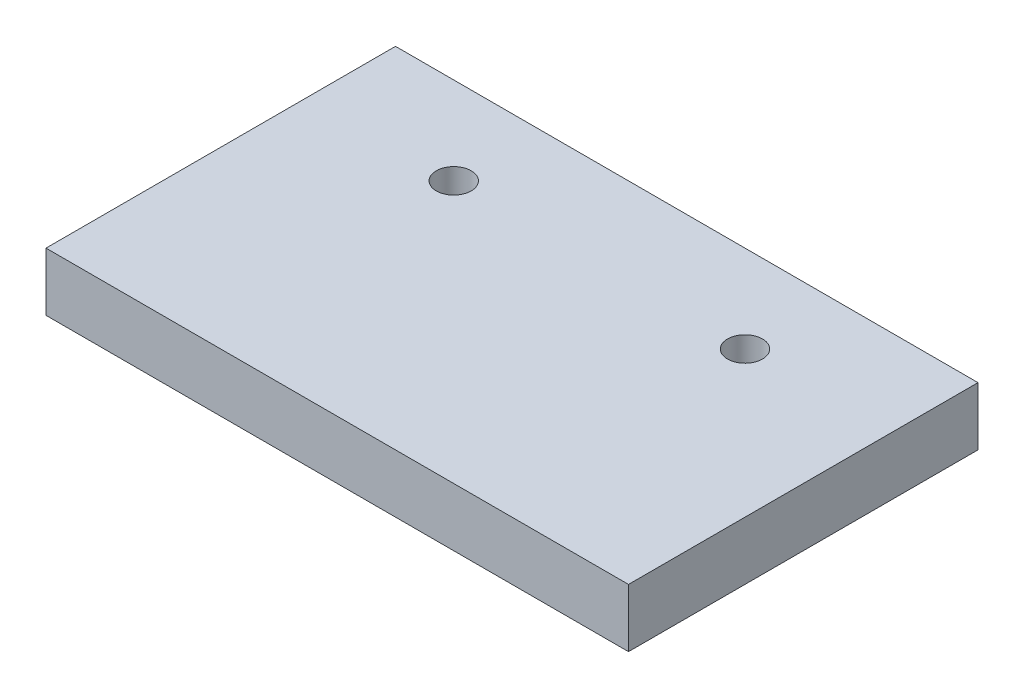
SolidWorks part; units mm, degrees
ref_plane "前视基准面" through (0, 0, 0) normal (0, 0, 1) x (1, 0, 0)
ref_plane "上视基准面" through (0, 0, 0) normal (0, 1, 0) x (1, 0, 0)
ref_plane "右视基准面" through (0, 0, 0) normal (1, 0, 0) x (0, 0, -1)
other "Configuration Table"
sketch "草图1" plane through (0, 0, 0) normal (0, 1, 0) x (1, 0, 0)
  line L1 (-50, -30) -> (50, -30)
  line L2 (-50, -30) -> (-50, 30)
  line L3 (-50, 30) -> (50, 30)
  line L4 (50, -30) -> (50, 30)
  line L5 (0, 30) -> (0, -30) construction
  line L6 (-50, 0) -> (50, 0) construction
  point P0 (0, 0)
extrude "凸台-拉伸1" add sketch "草图1" along normal blind 10
sketch "草图2" plane through (0, 0, 0) normal (0, 1, 0) x (1, 0, 0)
  circle A0 centre (25, 15) radius 3
extrude "切除-拉伸1" cut sketch "草图2" along normal blind 20
mirror "镜向1" about plane through (0, 0, 0) normal (1, 0, 0) of "切除-拉伸1"
